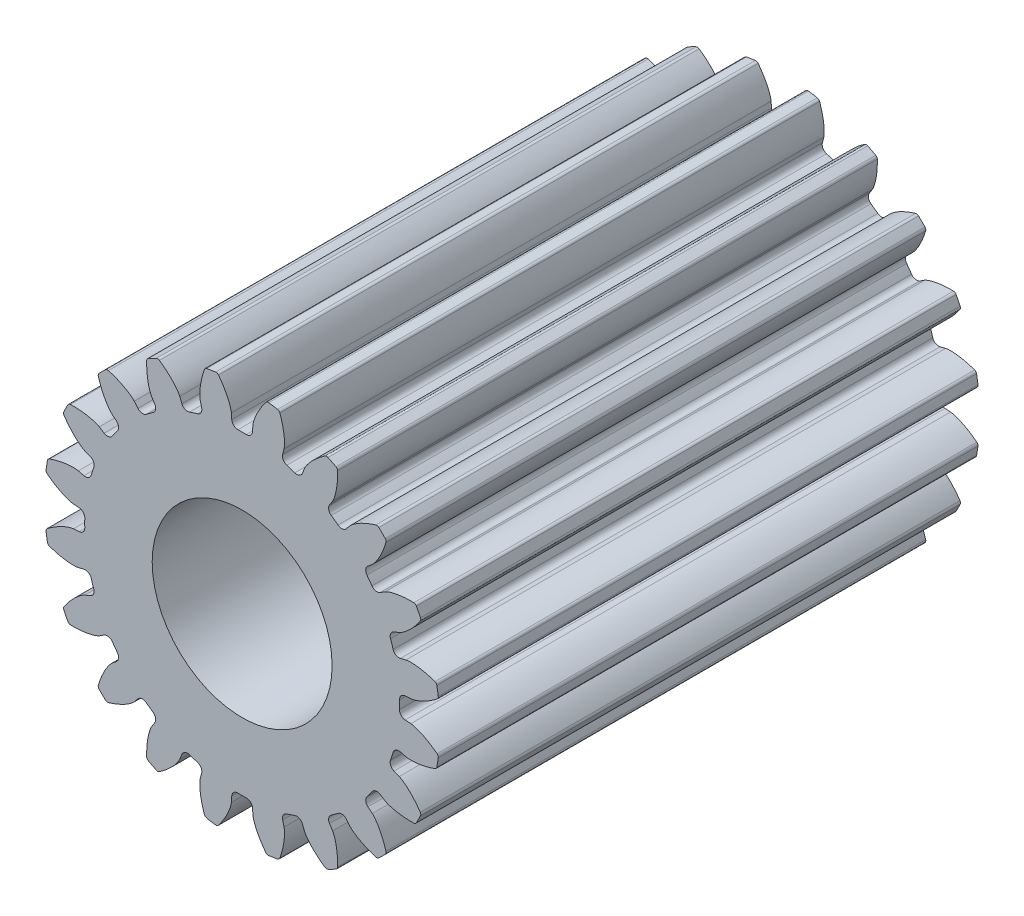
SolidWorks part; units mm, degrees
material "Alloy Steel"
ref_plane "Front" through (0, 0, 0) normal (0, 0, 1) x (1, 0, 0)
ref_plane "Top" through (0, 0, 0) normal (0, 1, 0) x (1, 0, 0)
ref_plane "Right" through (0, 0, 0) normal (1, 0, 0) x (0, 0, -1)
sketch "Sketch1" plane through (0, 0, 0) normal (0, 0, 1) x (1, 0, 0)
  circle A0 centre (0, 0) radius 5.5
extrude "Boss-Extrude1" add sketch "Sketch1" along normal blind 15
sketch "Sketch3" plane through (0, 0, 0) normal (0, 0, 1) x (1, 0, 0)
  line L0 (0, 0) -> (43.7181, 0) construction
  line L2 (0, 0) -> (-0.2782, 4.3661) construction
  line L3 (0, 0) -> (0.2782, 4.3661) construction
  line L4 (0.2782, 4.3661) -> (0.2988, 4.689) construction
  line L5 (0, 0) -> (0, 61.276) construction
  line L6 (-0.2782, 4.3661) -> (-0.2988, 4.689) construction
  circle A0 centre (0, 0) radius 5.5 construction
  circle A1 centre (0, 0) radius 5 construction
  circle A2 centre (0, 0) radius 4.6985 construction
  arc A3 (0.2782, 4.3661) -> (-0.2782, 4.3661) centre (0, 0) ccw construction
  arc A5 (0.6884, 5.4567) -> (-0.6884, 5.4567) centre (0, 0) ccw
  spline S0 degree 4 poles (-0.2988, 4.689) (-0.2989, 4.6902) (-0.2992, 4.6938) (-0.3, 4.7006) (-0.3017, 4.7116) (-0.3041, 4.7257) (-0.3078, 4.7437) (-0.3128, 4.7649) (-0.3189, 4.7881) (-0.3263, 4.8132) (-0.3342, 4.8381) (-0.3427, 4.8629) (-0.3517, 4.8875) (-0.3632, 4.9172) (-0.3778, 4.9525) (-0.3961, 4.9936) (-0.4183, 5.0398) (-0.4424, 5.0866) (-0.4674, 5.1322) (-0.4941, 5.1779) (-0.5209, 5.2219) (-0.5502, 5.2671) (-0.578, 5.3086) (-0.6107, 5.3545) (-0.6376, 5.3915) (-0.6747, 5.4396) (-0.6971, 5.4678) (-0.7239, 5.5007) (-0.7362, 5.5152) (-0.7437, 5.5241) knots 0 0 0 0 0 0.005377 0.015084 0.028532 0.04661 0.064855 0.092111 0.119476 0.146842 0.174209 0.201575 0.228941 0.256307 0.307035 0.361767 0.4165 0.471232 0.525964 0.580697 0.635429 0.690161 0.744894 0.799626 0.854358 0.909091 0.954545 1 1 1 1 1 construction
  spline S1 degree 4 poles (-0.2988, 4.689) (-0.2989, 4.6902) (-0.2992, 4.6938) (-0.3, 4.7006) (-0.3017, 4.7116) (-0.3041, 4.7257) (-0.3078, 4.7437) (-0.3128, 4.7649) (-0.3189, 4.7881) (-0.3263, 4.8132) (-0.3342, 4.8381) (-0.3427, 4.8629) (-0.3517, 4.8875) (-0.3632, 4.9172) (-0.3778, 4.9525) (-0.3961, 4.9936) (-0.4183, 5.0398) (-0.4424, 5.0866) (-0.4674, 5.1322) (-0.4941, 5.1779) (-0.5209, 5.2219) (-0.5502, 5.2671) (-0.578, 5.3086) (-0.6107, 5.3545) (-0.6376, 5.3915) (-0.6667, 5.4292) (-0.681, 5.4474) (-0.6884, 5.4567) knots 0 0 0 0 0 0.005377 0.015084 0.028532 0.04661 0.064855 0.092111 0.119476 0.146842 0.174209 0.201575 0.228941 0.256307 0.307035 0.361767 0.4165 0.471232 0.525964 0.580697 0.635429 0.690161 0.744894 0.799626 0.854358 0.909091 0.909091 0.909091 0.909091 0.909091
  spline S2 degree 4 poles (0.2988, 4.689) (0.2989, 4.6902) (0.2992, 4.6938) (0.3, 4.7006) (0.3017, 4.7116) (0.3041, 4.7257) (0.3078, 4.7437) (0.3128, 4.7649) (0.3189, 4.7881) (0.3263, 4.8132) (0.3342, 4.8381) (0.3427, 4.8629) (0.3517, 4.8875) (0.3632, 4.9172) (0.3778, 4.9525) (0.3961, 4.9936) (0.4183, 5.0398) (0.4424, 5.0866) (0.4674, 5.1322) (0.4941, 5.1779) (0.5209, 5.2219) (0.5502, 5.2671) (0.578, 5.3086) (0.6107, 5.3545) (0.6376, 5.3915) (0.6747, 5.4396) (0.6971, 5.4678) (0.7239, 5.5007) (0.7362, 5.5152) (0.7437, 5.5241) knots 0 0 0 0 0 0.005377 0.015084 0.028532 0.04661 0.064855 0.092111 0.119476 0.146842 0.174209 0.201575 0.228941 0.256307 0.307035 0.361767 0.4165 0.471232 0.525964 0.580697 0.635429 0.690161 0.744894 0.799626 0.854358 0.909091 0.954545 1 1 1 1 1 construction
  spline S3 degree 4 poles (0.2988, 4.689) (0.2989, 4.6902) (0.2992, 4.6938) (0.3, 4.7006) (0.3017, 4.7116) (0.3041, 4.7257) (0.3078, 4.7437) (0.3128, 4.7649) (0.3189, 4.7881) (0.3263, 4.8132) (0.3342, 4.8381) (0.3427, 4.8629) (0.3517, 4.8875) (0.3632, 4.9172) (0.3778, 4.9525) (0.3961, 4.9936) (0.4183, 5.0398) (0.4424, 5.0866) (0.4674, 5.1322) (0.4941, 5.1779) (0.5209, 5.2219) (0.5502, 5.2671) (0.578, 5.3086) (0.6107, 5.3545) (0.6376, 5.3915) (0.6667, 5.4292) (0.681, 5.4474) (0.6884, 5.4567) knots 0 0 0 0 0 0.005377 0.015084 0.028532 0.04661 0.064855 0.092111 0.119476 0.146842 0.174209 0.201575 0.228941 0.256307 0.307035 0.361767 0.4165 0.471232 0.525964 0.580697 0.635429 0.690161 0.744894 0.799626 0.854358 0.909091 0.909091 0.909091 0.909091 0.909091
  point P0 (0, 4.375)
sketch "DCLTBC" plane through (0, 0, 0) normal (0, 0, 1) x (1, 0, 0)
  line L0 (0, 0) -> (41.04, 0) construction
  line L1 (-0.2782, 4.3661) -> (-0.2988, 4.689) construction
  line L2 (0.2782, 4.3661) -> (0.2988, 4.689) construction
  line L3 (-0.2782, 4.3661) -> (-0.2988, 4.689)
  line L4 (0.2782, 4.3661) -> (0.2988, 4.689)
  line L5 (0, 0) -> (0, 104.9356) construction
  circle A0 centre (0, 0) radius 5.5
  circle A1 centre (0, 0) radius 5 construction
  circle A2 centre (0, 0) radius 4.6985 construction
  arc A3 (0.2782, 4.3661) -> (-0.2782, 4.3661) centre (0, 0) ccw construction
  arc A4 (0.2782, 4.3661) -> (-0.2782, 4.3661) centre (0, 0) ccw
  spline S0 degree 4 poles (-996.9487, -76.9973) (-9.3026, 3.5498) (-0.3864, 4.3017) (-0.2726, 4.5146) (-0.3017, 4.7116) (-0.3041, 4.7257) (-0.3078, 4.7437) (-0.3128, 4.7649) (-0.3189, 4.7881) (-0.3263, 4.8132) (-0.3342, 4.8381) (-0.3427, 4.8629) (-0.3517, 4.8875) (-0.3632, 4.9172) (-0.3778, 4.9525) (-0.3961, 4.9936) (-0.4183, 5.0398) (-0.4424, 5.0866) (-0.4674, 5.1322) (-0.4941, 5.1779) (-0.5209, 5.2219) (-0.5502, 5.2671) (-0.578, 5.3086) (-0.6107, 5.3545) (-0.7821, 5.5901) (-1.542, 6.4837) (11.8023, -10.3915) (-623.4998, 787.7996) knots -0.786066 -0.786066 -0.786066 -0.786066 -0.786066 0.005377 0.015084 0.028532 0.04661 0.064855 0.092111 0.119476 0.146842 0.174209 0.201575 0.228941 0.256307 0.307035 0.361767 0.4165 0.471232 0.525964 0.580697 0.635429 0.690161 0.744894 0.799626 0.854358 2.086332 2.086332 2.086332 2.086332 2.086332 only from (-0.2988, 4.689) to (-0.6884, 5.4567) construction
  spline S1 degree 4 poles (996.9487, -76.9973) (9.3026, 3.5498) (0.3864, 4.3017) (0.2726, 4.5146) (0.3017, 4.7116) (0.3041, 4.7257) (0.3078, 4.7437) (0.3128, 4.7649) (0.3189, 4.7881) (0.3263, 4.8132) (0.3342, 4.8381) (0.3427, 4.8629) (0.3517, 4.8875) (0.3632, 4.9172) (0.3778, 4.9525) (0.3961, 4.9936) (0.4183, 5.0398) (0.4424, 5.0866) (0.4674, 5.1322) (0.4941, 5.1779) (0.5209, 5.2219) (0.5502, 5.2671) (0.578, 5.3086) (0.6107, 5.3545) (0.7821, 5.5901) (1.542, 6.4837) (-11.8023, -10.3915) (623.4998, 787.7996) knots -0.786066 -0.786066 -0.786066 -0.786066 -0.786066 0.005377 0.015084 0.028532 0.04661 0.064855 0.092111 0.119476 0.146842 0.174209 0.201575 0.228941 0.256307 0.307035 0.361767 0.4165 0.471232 0.525964 0.580697 0.635429 0.690161 0.744894 0.799626 0.854358 2.086332 2.086332 2.086332 2.086332 2.086332 only from (0.2988, 4.689) to (0.6884, 5.4567) construction
  spline S2 degree 4 poles (-0.2988, 4.689) (-0.2989, 4.6902) (-0.2992, 4.6938) (-0.3, 4.7006) (-0.3017, 4.7116) (-0.3041, 4.7257) (-0.3078, 4.7437) (-0.3128, 4.7649) (-0.3189, 4.7881) (-0.3263, 4.8132) (-0.3342, 4.8381) (-0.3427, 4.8629) (-0.3517, 4.8875) (-0.3632, 4.9172) (-0.3778, 4.9525) (-0.3961, 4.9936) (-0.4183, 5.0398) (-0.4424, 5.0866) (-0.4674, 5.1322) (-0.4941, 5.1779) (-0.5209, 5.2219) (-0.5502, 5.2671) (-0.578, 5.3086) (-0.6107, 5.3545) (-0.6376, 5.3915) (-0.6667, 5.4292) (-0.681, 5.4474) (-0.6884, 5.4567) knots 0 0 0 0 0 0.005377 0.015084 0.028532 0.04661 0.064855 0.092111 0.119476 0.146842 0.174209 0.201575 0.228941 0.256307 0.307035 0.361767 0.4165 0.471232 0.525964 0.580697 0.635429 0.690161 0.744894 0.799626 0.854358 0.909091 0.909091 0.909091 0.909091 0.909091
  spline S3 degree 4 poles (0.2988, 4.689) (0.2989, 4.6902) (0.2992, 4.6938) (0.3, 4.7006) (0.3017, 4.7116) (0.3041, 4.7257) (0.3078, 4.7437) (0.3128, 4.7649) (0.3189, 4.7881) (0.3263, 4.8132) (0.3342, 4.8381) (0.3427, 4.8629) (0.3517, 4.8875) (0.3632, 4.9172) (0.3778, 4.9525) (0.3961, 4.9936) (0.4183, 5.0398) (0.4424, 5.0866) (0.4674, 5.1322) (0.4941, 5.1779) (0.5209, 5.2219) (0.5502, 5.2671) (0.578, 5.3086) (0.6107, 5.3545) (0.6376, 5.3915) (0.6667, 5.4292) (0.681, 5.4474) (0.6884, 5.4567) knots 0 0 0 0 0 0.005377 0.015084 0.028532 0.04661 0.064855 0.092111 0.119476 0.146842 0.174209 0.201575 0.228941 0.256307 0.307035 0.361767 0.4165 0.471232 0.525964 0.580697 0.635429 0.690161 0.744894 0.799626 0.854358 0.909091 0.909091 0.909091 0.909091 0.909091
extrude "Cut-Extrude-DCLTBC" cut sketch "DCLTBC" along normal through all
fillet "Fillet-Tip-DCLTBC" radius 0.0839 2 edges at (0.6884, 5.4567, 7.5) (-0.6884, 5.4567, 7.5)
fillet "Fillet-Root-DCLTBC" radius 0.1678 2 edges at (-0.2782, 4.3661, 7.5) (0.2782, 4.3661, 7.5)
pattern_circular "CirPattern-DCLTBC" count 20 over 360 about axis through (0, 0, 15) along (0, 0, 1) of "Cut-Extrude-DCLTBC", "Fillet-Tip-DCLTBC", "Fillet-Root-DCLTBC"
sketch "DCGTBC" [suppressed] plane through (0, 0, 0) normal (0, 0, 1) x (1, 0, 0)
  line L0 (0, 0) -> (41.04, 0) construction
  line L1 (-118.2981, 10.3497) -> (0, 0) construction
  line L2 (0, 0) -> (118.2981, 10.3497) construction
  line L3 (0, 0) -> (-16.5124, 0)
  line L5 (0, 0) -> (0, 104.9356) construction
  circle A0 centre (0, 0) radius 130
  circle A1 centre (0, 0) radius 125 construction
  circle A2 centre (0, 0) radius 117.4616 construction
  arc A3 (1.9607, 118.7338) -> (-1.9607, 118.7338) centre (0, 0) ccw construction
  arc A11 (118.2981, 10.3497) -> (-118.2981, 10.3497) centre (0, 0) ccw
  spline S4 degree 4 poles (1000.8658, 71.4969) (19.2618, 112.6201) (2.2033, 114.4544) (1.8257, 116.1103) (1.9619, 117.792) (1.9844, 118.0069) (2.0191, 118.2845) (2.0674, 118.6114) (2.1283, 118.9703) (2.2028, 119.3605) (2.2847, 119.7495) (2.3732, 120.1373) (2.4676, 120.5233) (2.5893, 120.9905) (2.7454, 121.5503) (2.9429, 122.2037) (3.1845, 122.9439) (3.4495, 123.6971) (3.7258, 124.4373) (4.0228, 125.184) (4.3228, 125.9056) (4.6527, 126.6539) (4.9665, 127.3439) (5.3384, 128.1155) (6.4568, 130.3899) (9.6326, 136.112) (-11.5818, 95.9351) (478.0107, 1011.5506) knots -0.41793 -0.41793 -0.41793 -0.41793 -0.41793 0.005377 0.015084 0.028532 0.04661 0.064855 0.092111 0.119476 0.146842 0.174209 0.201575 0.228941 0.256307 0.307035 0.361767 0.4165 0.471232 0.525964 0.580697 0.635429 0.690161 0.744894 0.799626 0.854358 1.490341 1.490341 1.490341 1.490341 1.490341 only from (1.9394, 117.4456) to (6.2272, 129.8508) construction
  spline S5 degree 4 poles (-1000.8658, 71.4969) (-19.2618, 112.6201) (-2.2033, 114.4544) (-1.8257, 116.1103) (-1.9619, 117.792) (-1.9844, 118.0069) (-2.0191, 118.2845) (-2.0674, 118.6114) (-2.1283, 118.9703) (-2.2028, 119.3605) (-2.2847, 119.7495) (-2.3732, 120.1373) (-2.4676, 120.5233) (-2.5893, 120.9905) (-2.7454, 121.5503) (-2.9429, 122.2037) (-3.1845, 122.9439) (-3.4495, 123.6971) (-3.7258, 124.4373) (-4.0228, 125.184) (-4.3228, 125.9056) (-4.6527, 126.6539) (-4.9665, 127.3439) (-5.3384, 128.1155) (-6.4568, 130.3899) (-9.6326, 136.112) (11.5818, 95.9351) (-478.0107, 1011.5506) knots -0.41793 -0.41793 -0.41793 -0.41793 -0.41793 0.005377 0.015084 0.028532 0.04661 0.064855 0.092111 0.119476 0.146842 0.174209 0.201575 0.228941 0.256307 0.307035 0.361767 0.4165 0.471232 0.525964 0.580697 0.635429 0.690161 0.744894 0.799626 0.854358 1.490341 1.490341 1.490341 1.490341 1.490341 only from (-1.9394, 117.4456) to (-6.2272, 129.8508) construction
  spline S6 degree 4 poles (1.9394, 117.4456) (1.9399, 117.4651) (1.942, 117.5198) (1.9483, 117.6233) (1.9619, 117.792) (1.9844, 118.0069) (2.0191, 118.2845) (2.0674, 118.6114) (2.1283, 118.9703) (2.2028, 119.3605) (2.2847, 119.7495) (2.3732, 120.1373) (2.4676, 120.5233) (2.5893, 120.9905) (2.7454, 121.5503) (2.9429, 122.2037) (3.1845, 122.9439) (3.4495, 123.6971) (3.7258, 124.4373) (4.0228, 125.184) (4.3228, 125.9056) (4.6527, 126.6539) (4.9665, 127.3439) (5.3384, 128.1155) (5.6444, 128.7378) (5.9774, 129.3793) (6.142, 129.6914) (6.2272, 129.8508) knots 0 0 0 0 0 0.005377 0.015084 0.028532 0.04661 0.064855 0.092111 0.119476 0.146842 0.174209 0.201575 0.228941 0.256307 0.307035 0.361767 0.4165 0.471232 0.525964 0.580697 0.635429 0.690161 0.744894 0.799626 0.854358 0.909091 0.909091 0.909091 0.909091 0.909091
  spline S7 degree 4 poles (-1.9394, 117.4456) (-1.9399, 117.4651) (-1.942, 117.5198) (-1.9483, 117.6233) (-1.9619, 117.792) (-1.9844, 118.0069) (-2.0191, 118.2845) (-2.0674, 118.6114) (-2.1283, 118.9703) (-2.2028, 119.3605) (-2.2847, 119.7495) (-2.3732, 120.1373) (-2.4676, 120.5233) (-2.5893, 120.9905) (-2.7454, 121.5503) (-2.9429, 122.2037) (-3.1845, 122.9439) (-3.4495, 123.6971) (-3.7258, 124.4373) (-4.0228, 125.184) (-4.3228, 125.9056) (-4.6527, 126.6539) (-4.9665, 127.3439) (-5.3384, 128.1155) (-5.6444, 128.7378) (-5.9774, 129.3793) (-6.142, 129.6914) (-6.2272, 129.8508) knots 0 0 0 0 0 0.005377 0.015084 0.028532 0.04661 0.064855 0.092111 0.119476 0.146842 0.174209 0.201575 0.228941 0.256307 0.307035 0.361767 0.4165 0.471232 0.525964 0.580697 0.635429 0.690161 0.744894 0.799626 0.854358 0.909091 0.909091 0.909091 0.909091 0.909091
  dimension "D1" = 5
  dimension "D2" = 5
extrude "Cut-Extrude-DCGTBC" [suppressed] cut sketch "DCGTBC" along normal through all
fillet "Fillet-Tip-DCGTBC" [suppressed] radius 0.0839
pattern_circular "CirPattern-DCGTBC" [suppressed] count 20 over 360
sketch "Sketch4" plane through (0, 0, 15) normal (0, 0, 1) x (1, 0, 0)
  circle A0 centre (0, 0) radius 2.5
  dimension "D1" = 5
extrude "Cut-Extrude2" cut sketch "Sketch4" against normal through all
equation "\"DiametralPitch\" = 25.4 / 0.5'Diametral Pitch"
equation "\"NumTeeth\" = 20'Number of Teeth"
equation "\"PressureAngle\" = 20deg'Pressure Angle"
equation "\"Addendum\"= 1 / \"DiametralPitch\"'Addendum"
equation "\"Dedendum\"= 1.25 / \"DiametralPitch\"'Dedendum"
equation "\"WorkingDepth\"= 2 / \"DiametralPitch\"'Working Depth - here for REF (Not used in building model)"
equation "\"WholeDepth\"= 2.25 / \"DiametralPitch\"'Whole Depth - here for REF (Not used in building model)"
equation "\"Clearance\"= .25 / \"DiametralPitch\"'Clearance"
equation "\"CircularPitch\"= pi / \"DiametralPitch\"'Circular Pitch - here for REF (Not used in building model)"
equation "\"PitchCircle\"= \"NumTeeth\" / \"DiametralPitch\"'Pitch Circle - or - Pitch Diameter"
equation "\"OutsideDiameter\"= ( \"NumTeeth\" + 2 ) / \"DiametralPitch\"'Outside Diameter"
equation "\"Fillet_Root\"= \"Clearance\" * cos ( \"PressureAngle\" ) * tan ( ( 90 + \"PressureAngle\" ) / 2 ) 'Fillet Root"
equation "\"AddendumCircle\"= \"PitchCircle\" + ( 2 * \"Addendum\" )'Addendum Circle - or - Addendum Diameter"
equation "\"DedendumCircle\"= \"PitchCircle\" - ( 2 * \"Dedendum\" )'Dedendum Circle - or - Dedendum Diameter"
equation "\"BaseCircle\"= \"PitchCircle\" * cos ( \"PressureAngle\" )'Base Circle - Base Diameter"
equation "\"PitchAngle\"= 360deg / \"NumTeeth\"'Pitch Angle"
equation "\"Alpha\"= sqr ( \"PitchCircle\" ^ 2 - \"BaseCircle\" ^ 2 ) / \"BaseCircle\" * 180 / PI - \"PressureAngle\"'Alpha - Used for Calculating Beta"
equation "\"Beta\"= ( \"PitchAngle\" / 4 - ( \"Alpha\" - 90 ) )'Beta - Used in definition of the parameters for the parametric equation driven curve"
equation "\"Gamma\"= ( \"PitchAngle\" / 4 - ( \"Alpha\" + 90 ) )'Gamma - Used in definition of the parameters for the parametric equation driven curve"
equation "\"Phi\"= sqr ( ( \"AddendumCircle\" / 2 ) ^ 2 - ( \"BaseCircle\" / 2 ) ^ 2 ) / ( \"BaseCircle\" / 2 )'Phi - Used in definition of the parameters for the parametric equation driven curve"
equation "\"DCGTBC\"= iif ( \"DedendumCircle\" > \"BaseCircle\" , \"unsuppressed\" , \"suppressed\" )'if Dedendum Circle IS GREATER THAN BaseCircle THEN UnsuppressORSuppress FEATURE"
equation "\"DCLTBC\"= iif ( \"DedendumCircle\" - .002 > \"BaseCircle\" , \"suppressed\" , \"unsuppressed\" )'if Dedendum Circle - .002 IS GREATER THAN BaseCircle THEN SuppressORUnsuppress FEATURE"
equation "\"Cut-Extrude-DCGTBC\"= iif ( \"DedendumCircle\" > \"BaseCircle\" , \"unsuppressed\" , \"suppressed\" )'if Dedendum Circle IS GREATER THAN BaseCircle THEN UnsuppressORSuppress FEATURE"
equation "\"Cut-Extrude-DCLTBC\"= iif ( \"DedendumCircle\" - .002 > \"BaseCircle\" , \"suppressed\" , \"unsuppressed\" )'if Dedendum Circle - .002 IS GREATER THAN BaseCircle THEN SuppressORUnsuppress FEATURE"
equation "\"CirPattern-DCGTBC\"= iif ( \"DedendumCircle\" > \"BaseCircle\" , \"unsuppressed\" , \"suppressed\" )'if Dedendum Circle IS GREATER THAN BaseCircle THEN UnsuppressORSuppress FEATURE"
equation "\"CirPattern-DCLTBC\"= iif ( \"DedendumCircle\" - .002 > \"BaseCircle\" , \"suppressed\" , \"unsuppressed\" )'if Dedendum Circle - .002 IS GREATER THAN BaseCircle THEN SuppressORUnsuppress FEATURE"
equation "\"Fillet-Tip-DCGTBC\"= iif ( \"DedendumCircle\" > \"BaseCircle\" , \"unsuppressed\" , \"suppressed\" )'if Dedendum Circle IS GREATER THAN BaseCircle THEN UnsuppressORSuppress FEATURE"
equation "\"Fillet-Tip-DCLTBC\"= iif ( \"DedendumCircle\" - .002 > \"BaseCircle\" , \"suppressed\" , \"unsuppressed\" )'if Dedendum Circle - .002 IS GREATER THAN BaseCircle THEN SuppressORUnsuppress FEATURE"
equation "\"Fillet-Root-DCLTBC\"= iif ( \"DedendumCircle\" - .002 > \"BaseCircle\" , \"suppressed\" , \"unsuppressed\" )'if Dedendum Circle - .002 IS GREATER THAN BaseCircle THEN SuppressORUnsuppress FEATURE"
equation "\"D1@CirPattern-DCGTBC\"= \"NumTeeth\"'Number of Teeth"
equation "\"D1@CirPattern-DCLTBC\"= \"NumTeeth\"'Number of Teeth"
equation "\"D1@Fillet-Tip-DCGTBC\"= \"Fillet_Root\" / 2 'Tip Rad For Large No of Teeth"
equation "\"D1@Fillet-Tip-DCLTBC\"=\"Fillet_Root\" / 2'Tip Rad For Small No of Teeth"
equation "\"D1@Fillet-Root-DCLTBC\"= \"Fillet_Root\"'Fillet Root"
